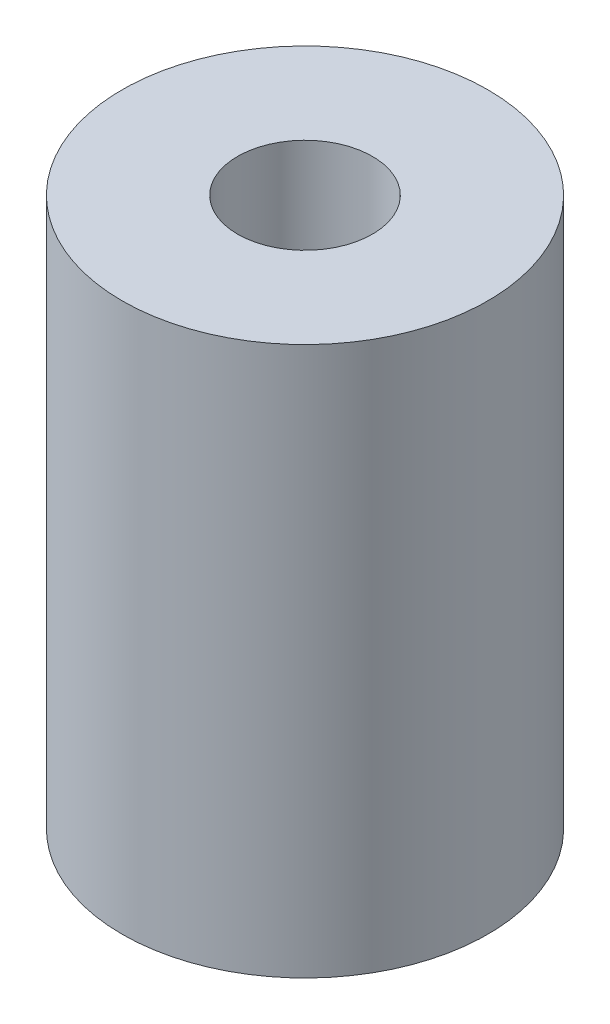
SolidWorks part; units mm, degrees
ref_plane "前视基准面" through (0, 0, 0) normal (0, 0, 1) x (1, 0, 0)
ref_plane "上视基准面" through (0, 0, 0) normal (0, 1, 0) x (1, 0, 0)
ref_plane "右视基准面" through (0, 0, 0) normal (1, 0, 0) x (0, 0, -1)
sketch "草图1" plane through (0, 0, 0) normal (0, 1, 0) x (1, 0, 0)
  circle A0 centre (0, 0) radius 1.475
  circle A1 centre (0, 0) radius 4
  dimension "D1" = 2.95
  dimension "D2" = 8
extrude "凸台-拉伸1" add sketch "草图1" along normal blind 12
